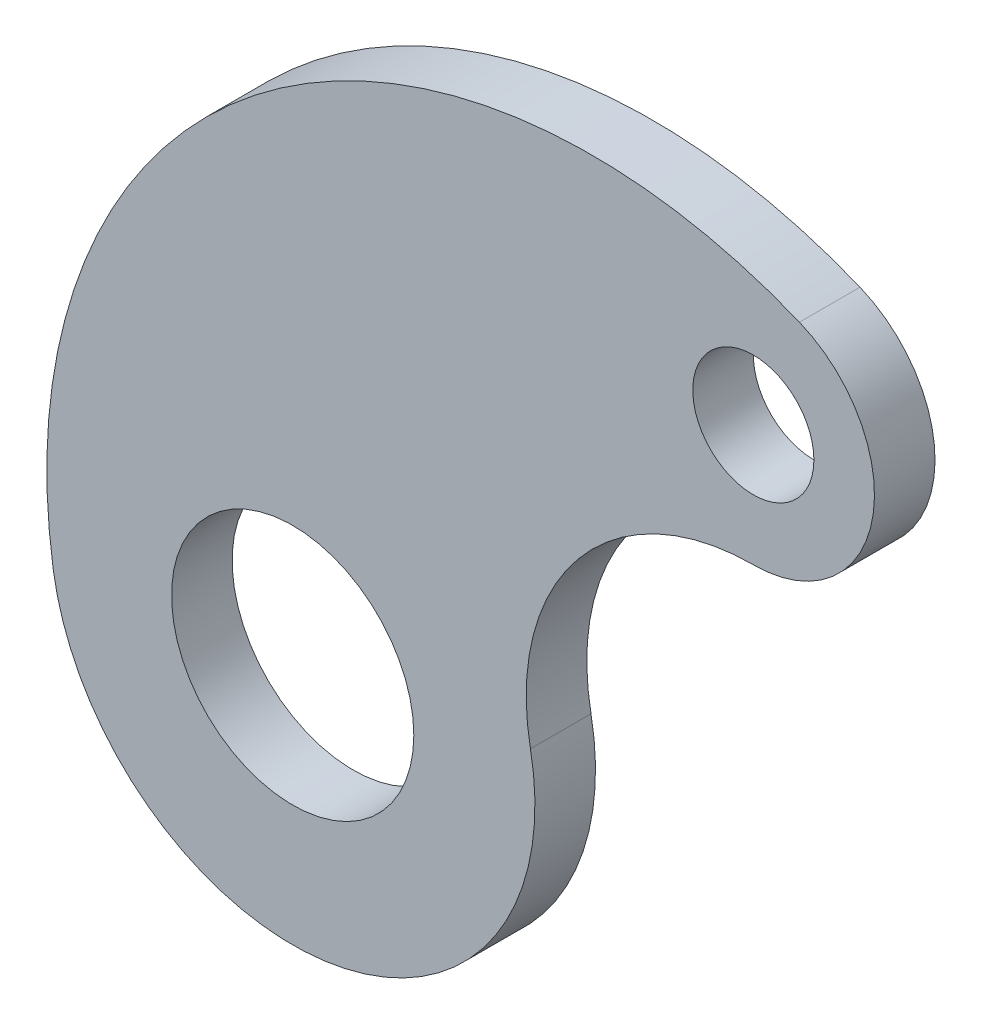
SolidWorks part; units mm, degrees
material "Hexcel AS4C (3000 Filaments)"
ref_plane "Front Plane" through (0, 0, 0) normal (0, 0, 1) x (1, 0, 0)
ref_plane "Top Plane" through (0, 0, 0) normal (0, 1, 0) x (1, 0, 0)
ref_plane "Right Plane" through (0, 0, 0) normal (1, 0, 0) x (0, 0, -1)
sketch "Sketch1" plane through (0, 0, 0) normal (0, 0, 1) x (1, 0, 0)
  line L0 (0, 0) -> (152.1118, 144.7826) construction
  line L1 (0, 0) -> (6.2726, -25.9558) construction
  arc A0 (-79.0553, -12.2581) -> (78.5093, 15.3717) centre (0, 0) ccw
  arc A1 (152.1118, 104.7826) -> (167.3383, 181.7712) centre (152.1118, 144.7826) ccw
  arc A2 (-79.0553, -12.2581) -> (167.3383, 181.7712) centre (98.8191, 15.3226) cw
  arc A3 (78.5093, 15.3717) -> (152.1118, 104.7826) centre (152.1118, 29.7826) cw
  circle A4 centre (0, 0) radius 40
  circle A5 centre (152.1118, 144.7826) radius 20
  dimension "D2" = 160
  dimension "D3" = 80
  dimension "D4" = 180
  dimension "D5" = 75
  dimension "D6" = 40
  dimension "D7" = 80
  dimension "D1" = 210
  dimension "D8" = 120
extrude "Boss-Extrude1" add sketch "Sketch1" along normal blind 20
